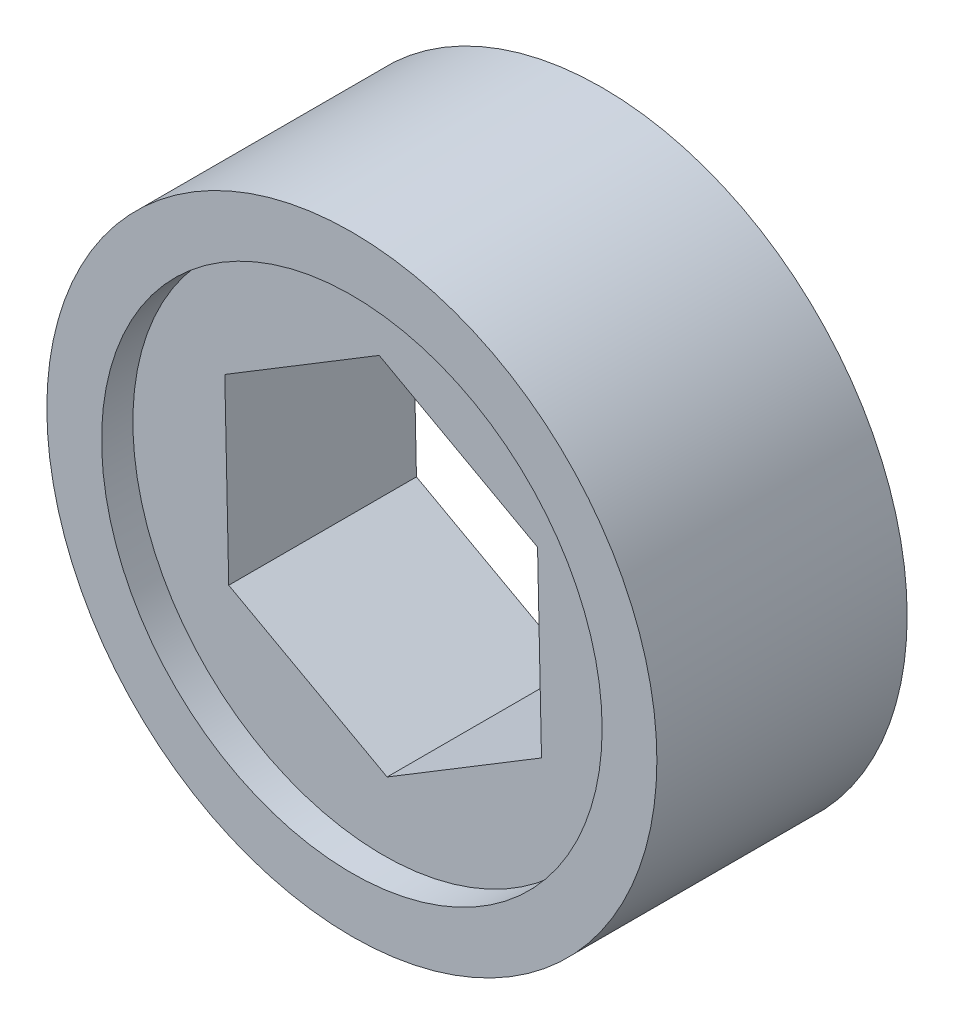
SolidWorks part; units mm, degrees
ref_plane "Front Plane" through (0, 0, 0) normal (0, 0, 1) x (1, 0, 0)
ref_plane "Top Plane" through (0, 0, 0) normal (0, 1, 0) x (1, 0, 0)
ref_plane "Right Plane" through (0, 0, 0) normal (1, 0, 0) x (0, 0, -1)
sketch "Sketch1" plane through (0, 0, 0) normal (0, 0, 1) x (1, 0, 0)
  line L1 (0.1604, -7.3306) -> (6.4287, -3.5264)
  line L2 (6.4287, -3.5264) -> (6.2683, 3.8042)
  line L3 (6.2683, 3.8042) -> (-0.1604, 7.3306)
  line L4 (-0.1604, 7.3306) -> (-6.4287, 3.5264)
  line L5 (-6.4287, 3.5264) -> (-6.2683, -3.8042)
  line L6 (-6.2683, -3.8042) -> (0.1604, -7.3306)
  circle A0 centre (0, 0) radius 12.3825
  circle A1 centre (0, 0) radius 6.35 construction
  dimension "D1" = 24.765
  dimension "D2" = 12.7
extrude "Boss-Extrude1" add sketch "Sketch1" along normal blind 10.16
sketch "Esquisse1" plane through (0, 0, 10.16) normal (0, 0, 1) x (1, 0, 0)
  circle A0 centre (0, 0) radius 10.16
  dimension "D1" = 20.32
extrude "Enlèv. mat.-Extru.1" cut sketch "Esquisse1" against normal blind 1.27
sketch "Esquisse2" plane through (0, 0, 0) normal (0, 0, -1) x (-1, 0, 0)
  circle A0 centre (0, 0) radius 10.16
  dimension "D1" = 20.32
extrude "Enlèv. mat.-Extru.2" cut sketch "Esquisse2" against normal blind 1.27
